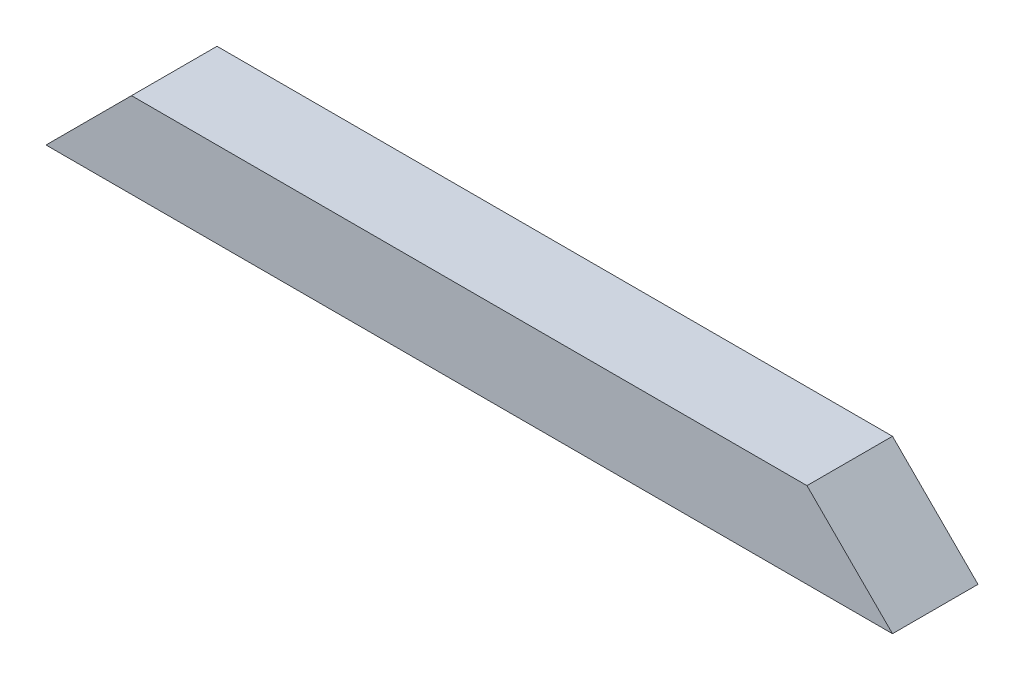
SolidWorks part; units mm, degrees
ref_plane "Ebene vorne" through (0, 0, 0) normal (0, 0, 1) x (1, 0, 0)
ref_plane "Ebene oben" through (0, 0, 0) normal (0, 1, 0) x (1, 0, 0)
ref_plane "Ebene rechts" through (0, 0, 0) normal (1, 0, 0) x (0, 0, -1)
sketch "Skizze1" plane through (0, 0, 0) normal (0, 0, 1) x (1, 0, 0)
  line L0 (0, 0) -> (395.9798, 0)
  line L1 (395.9798, 0) -> (355.9798, 40)
  line L2 (355.9798, 40) -> (40, 40)
  line L3 (40, 40) -> (0, 0)
  dimension "D1" = 395.9798
  dimension "D2" = 40
  dimension "D3" = 40
  dimension "D4" = 40
extrude "Aufsatz-Linear austragen1" add sketch "Skizze1" along normal blind 40
